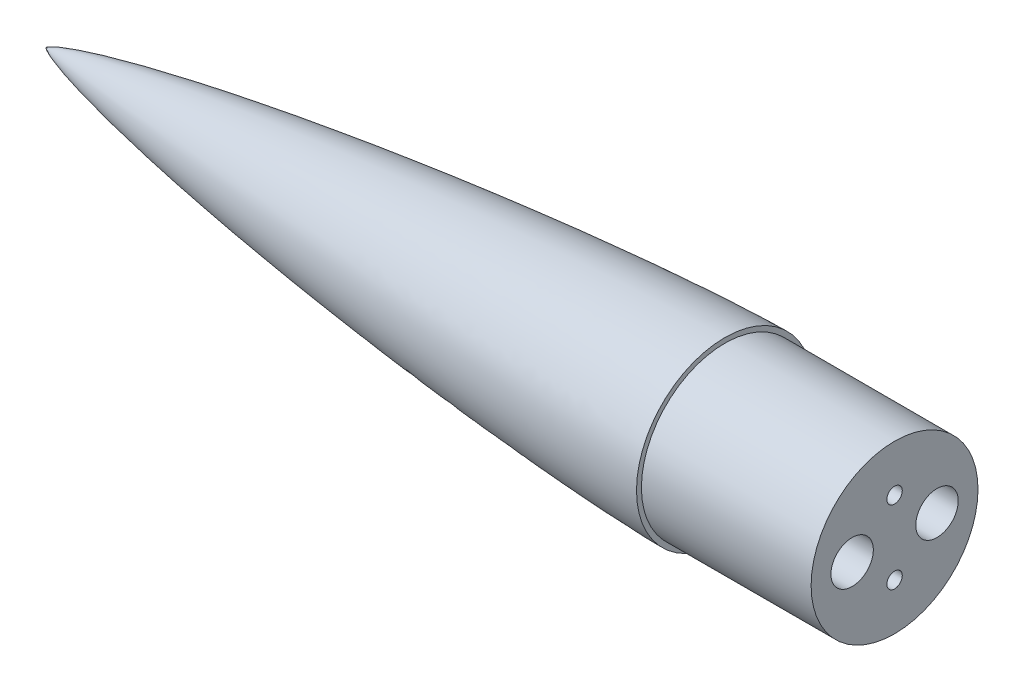
SolidWorks part; units mm, degrees
ref_plane "Front Plane" through (0, 0, 0) normal (0, 0, 1) x (1, 0, 0)
ref_plane "Top Plane" through (0, 0, 0) normal (0, 1, 0) x (1, 0, 0)
ref_plane "Right Plane" through (0, 0, 0) normal (1, 0, 0) x (0, 0, -1)
sketch "Sketch1" plane through (0, 0, 0) normal (0, 0, 1) x (1, 0, 0)
  line L0 (0, 0) -> (304.8, 0)
  line L1 (304.8, 0) -> (304.8, 39.6748)
  spline S0 degree 4 poles (0, 0) (0.002, 0.0064) (0.007, 0.0186) (0.0214, 0.0411) (0.055, 0.0825) (0.104, 0.1316) (0.1684, 0.1876) (0.2612, 0.2604) (0.3887, 0.3509) (0.5819, 0.4752) (0.9068, 0.6632) (1.4585, 0.9484) (2.4215, 1.3879) (4.1633, 2.0851) (7.3306, 3.1845) (12.6051, 4.7651) (22.0862, 7.23) (35.4349, 10.1996) (51.9432, 13.4279) (70.826, 16.7203) (89.7562, 19.7245) (108.7227, 22.49) (127.718, 25.0491) (146.7376, 27.4201) (165.7784, 29.6148) (184.8381, 31.6384) (203.9151, 33.4915) (223.0084, 35.1694) (242.1172, 36.661) (261.241, 37.9466) (277.4483, 38.8293) (289.8052, 39.3398) (298.3053, 39.5804) (302.0164, 39.6495) (303.8721, 39.672) (304.8, 39.6748) knots 0 0 0 0 0 0.000086 0.000172 0.000345 0.00069 0.000985 0.00128 0.001875 0.002717 0.003965 0.006149 0.009932 0.016448 0.028301 0.04964 0.081363 0.14354 0.205717 0.267893 0.33007 0.392247 0.454423 0.5166 0.578777 0.640954 0.70313 0.765307 0.827484 0.88966 0.951837 0.975919 0.987959 1 1 1 1 1 construction
  spline S1 degree 4 poles (0, 0) (0.002, 0.0064) (0.007, 0.0186) (0.0214, 0.0411) (0.055, 0.0825) (0.104, 0.1316) (0.1684, 0.1876) (0.2612, 0.2604) (0.3887, 0.3509) (0.5819, 0.4752) (0.9068, 0.6632) (1.4585, 0.9484) (2.4215, 1.3879) (4.1633, 2.0851) (7.3306, 3.1845) (12.6051, 4.7651) (22.0862, 7.23) (35.4349, 10.1996) (51.9432, 13.4279) (70.826, 16.7203) (89.7562, 19.7245) (108.7227, 22.49) (127.718, 25.0491) (146.7376, 27.4201) (165.7784, 29.6148) (184.8381, 31.6384) (203.9151, 33.4915) (223.0084, 35.1694) (242.1172, 36.661) (261.241, 37.9466) (277.4483, 38.8293) (289.8052, 39.3398) (298.3053, 39.5804) (302.0164, 39.6495) (303.8721, 39.672) (304.8, 39.6748) knots 0 0 0 0 0 0.000086 0.000172 0.000345 0.00069 0.000985 0.00128 0.001875 0.002717 0.003965 0.006149 0.009932 0.016448 0.028301 0.04964 0.081363 0.14354 0.205717 0.267893 0.33007 0.392247 0.454423 0.5166 0.578777 0.640954 0.70313 0.765307 0.827484 0.88966 0.951837 0.975919 0.987959 1 1 1 1 1
  dimension "D1" = 304.8
revolve "Revolve1" add sketch "Sketch1" angle 360 about L0
sketch "Sketch2" plane through (304.8, 0, 0) normal (1, 0, 0) x (0, 0, -1)
  circle A0 centre (0, 0) radius 37.465
  dimension "D1" = 74.93
extrude "Boss-Extrude1" add sketch "Sketch2" along normal blind 50.8
sketch "Sketch3" plane through (355.6, 0, 0) normal (1, 0, 0) x (0, 0, -1)
  line L0 (0, 37.465) -> (0, -37.465) construction
  circle A0 centre (0, 0) radius 37.465 construction
  circle A1 centre (0, 0) radius 37.465 construction
  circle A2 centre (-19.05, 0) radius 9.525
  dimension "D1" = 19.05
  dimension "D2" = 19.05
revolve "Cut-Revolve1" cut sketch "Sketch3" angle 180 about L0
sketch "Sketch4" plane through (355.6, 0, 0) normal (1, 0, 0) x (0, 0, -1)
  line L0 (0, 37.465) -> (0, -37.465) construction
  circle A0 centre (0, 0) radius 37.465
  circle A1 centre (-19.05, 0) radius 9.525
  circle A2 centre (19.05, 0) radius 9.525
  dimension "D1" = 74.93
  dimension "D4" = 19.05
  dimension "D5" = 19.05
  dimension "D2" = 19.05
  dimension "D3" = 19.05
extrude "Boss-Extrude2" add sketch "Sketch4" along normal blind 25.4
sketch "Sketch5" plane through (381, 0, 0) normal (1, 0, 0) x (0, 0, -1)
  circle A0 centre (0, 16.51) radius 3.4671
  circle A1 centre (0, -16.51) radius 3.4671
  dimension "D1" = 6.9342
  dimension "D2" = 6.9342
  dimension "D3" = 16.51
  dimension "D4" = 16.51
extrude "Cut-Extrude1" cut sketch "Sketch5" against normal blind 254
